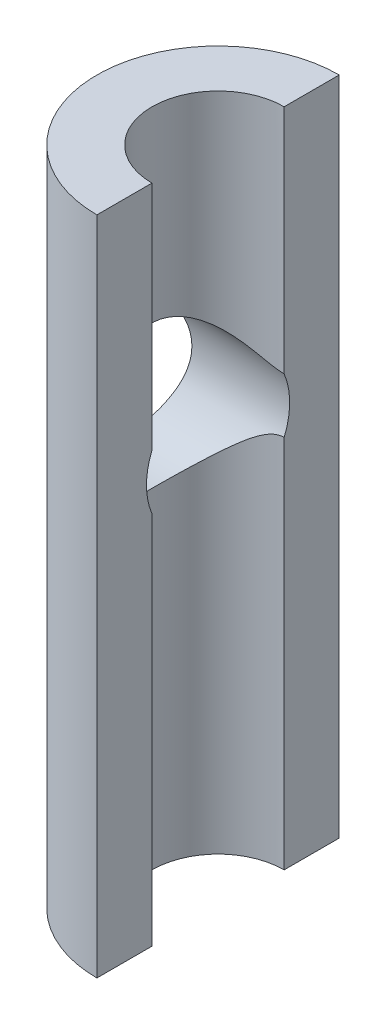
SolidWorks part; units mm, degrees
ref_plane "Front Plane" through (0, 0, 0) normal (0, 0, 1) x (1, 0, 0)
ref_plane "Top Plane" through (0, 0, 0) normal (0, 1, 0) x (1, 0, 0)
ref_plane "Right Plane" through (0, 0, 0) normal (1, 0, 0) x (0, 0, -1)
sketch "Sketch1" plane through (0, 0, 0) normal (0, 1, 0) x (1, 0, 0)
  line L0 (0, 5.5) -> (0, 3) construction
  line L1 (0, -3) -> (0, -5.5) construction
  line L2 (0, 5.5) -> (0, 3)
  line L3 (0, -3) -> (0, -5.5)
  arc A0 (0, 3) -> (0, -3) centre (0, 0) ccw
  arc A1 (0, 5.5) -> (0, -5.5) centre (0, 0) ccw
  dimension "D1" = 11
  dimension "D2" = 6
extrude "Boss-Extrude1" add sketch "Sketch1" along normal blind 30 contours L2 A1 L3 A0
sketch "Sketch2" plane through (0, 0, 0) normal (1, 0, 0) x (0, 0, -1)
  line L0 (0, 30) -> (0, 21.5) construction
  line L1 (3, 30) -> (-3, 30) construction
  circle A0 centre (0, 18.25) radius 3.25
  dimension "D2" = 6.5
  dimension "D1" = 8.5
extrude "Cut-Extrude1" cut sketch "Sketch2" against normal through all both and the other way through all
